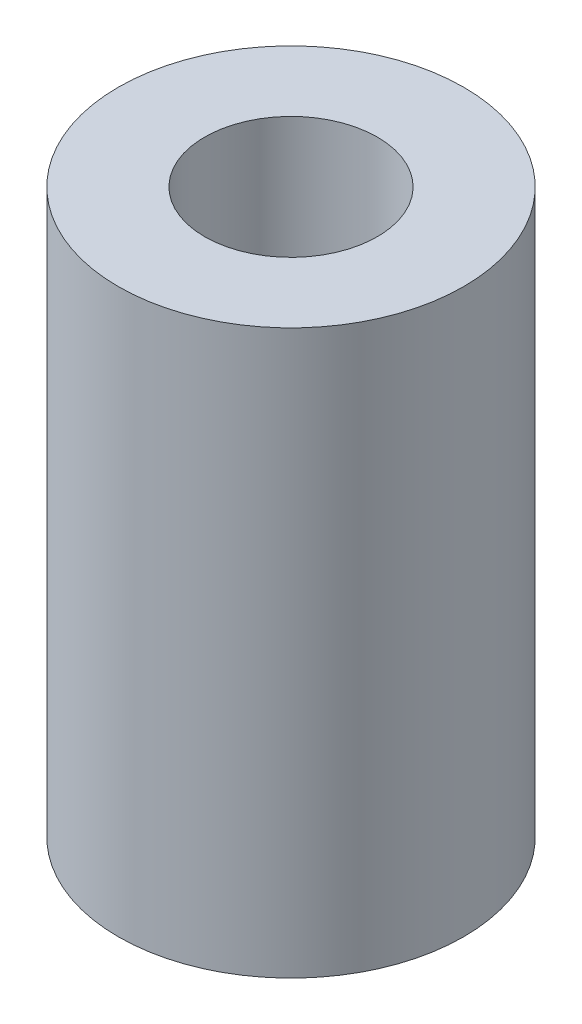
SolidWorks part; units mm, degrees
ref_plane "Front Plane" through (0, 0, 0) normal (0, 0, 1) x (1, 0, 0)
ref_plane "Top Plane" through (0, 0, 0) normal (0, 1, 0) x (1, 0, 0)
ref_plane "Right Plane" through (0, 0, 0) normal (1, 0, 0) x (0, 0, -1)
sketch "Sketch1" plane through (0, 0, 0) normal (0, 1, 0) x (1, 0, 0)
  circle A0 centre (0, 0) radius 4.6
  circle A1 centre (0, 0) radius 2.3
  dimension "D1" = 4.6
  dimension "D2" = 9.2
extrude "Boss-Extrude1" add sketch "Sketch1" along normal blind 15
